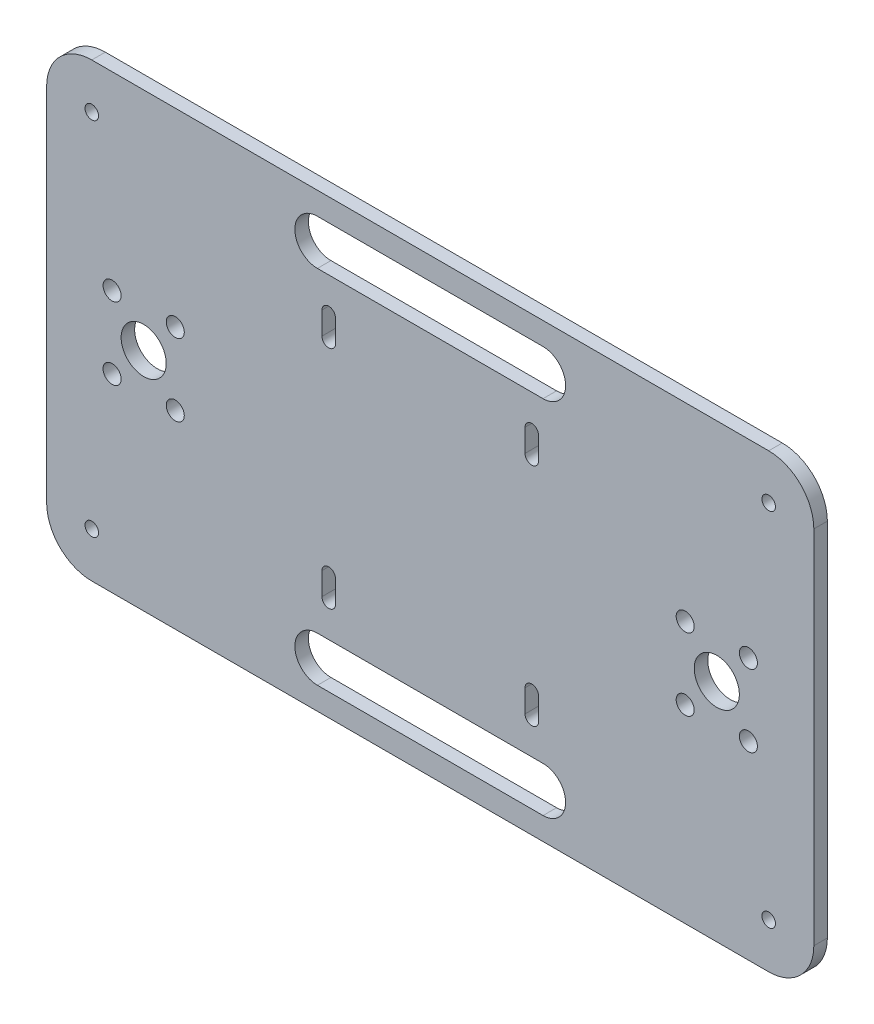
SolidWorks part; units mm, degrees
ref_plane "Front Plane" through (0, 0, 0) normal (0, 0, 1) x (1, 0, 0)
ref_plane "Top Plane" through (0, 0, 0) normal (0, 1, 0) x (1, 0, 0)
ref_plane "Right Plane" through (0, 0, 0) normal (1, 0, 0) x (0, 0, -1)
sketch "Sketch1" plane through (0, 0, 0) normal (0, 0, 1) x (1, 0, 0)
  line L0 (-85, 0) -> (85, 0) construction
  line L1 (-75, 50) -> (75, 50)
  line L2 (-85, 40) -> (-85, -40)
  line L3 (-75, -50) -> (75, -50)
  line L4 (85, 40) -> (85, -40)
  line L5 (-85, 50) -> (85, -50) construction
  line L6 (-85, -50) -> (85, 50) construction
  line L7 (0, 50) -> (0, -50) construction
  line L8 (-63.5, 20) -> (-63.5, -20) construction
  line L9 (-85, 20) -> (-42, 20)
  line L10 (-85, 20) -> (-85, -20)
  line L11 (-85, -20) -> (-42, -20)
  line L12 (-42, 20) -> (-42, -20)
  line L13 (-85, 20) -> (-42, -20) construction
  line L14 (-85, -20) -> (-42, 20) construction
  line L15 (85, -20) -> (42, -20)
  line L16 (42, 20) -> (42, -20)
  line L17 (85, 20) -> (42, 20)
  line L18 (85, 20) -> (85, -20)
  line L19 (-25, 40) -> (25, 40) construction
  line L20 (-25, 45) -> (25, 45)
  line L21 (-25, 35) -> (25, 35)
  line L22 (-25, -40) -> (25, -40) construction
  line L23 (-25, -45) -> (25, -45)
  line L24 (-25, -35) -> (25, -35)
  line L25 (-22.5, -27.5) -> (-22.5, -22.5) construction
  line L26 (-22.5, -25) -> (22.5, -25) construction
  line L27 (-22.5, -25) -> (-22.5, 25) construction
  line L28 (-22.5, 25) -> (22.5, 25) construction
  line L29 (22.5, -25) -> (22.5, 25) construction
  line L30 (-22.5, -25) -> (22.5, 25) construction
  line L31 (-22.5, 25) -> (22.5, -25) construction
  line L34 (-24, -27.5) -> (-24, -22.5)
  line L35 (-21, -27.5) -> (-21, -22.5)
  line L36 (-22.5, 27.5) -> (-22.5, 22.5) construction
  line L37 (-24, 27.5) -> (-24, 22.5)
  line L38 (-21, 27.5) -> (-21, 22.5)
  line L39 (22.5, 27.5) -> (22.5, 22.5) construction
  line L40 (24, 27.5) -> (24, 22.5)
  line L41 (21, 27.5) -> (21, 22.5)
  line L42 (22.5, -27.5) -> (22.5, -22.5) construction
  line L43 (24, -27.5) -> (24, -22.5)
  line L44 (21, -27.5) -> (21, -22.5)
  circle A0 centre (-70.5, 8) radius 2
  circle A1 centre (-70.5, -8) radius 2
  circle A2 centre (-56.5, -8) radius 2
  circle A3 centre (-56.5, 8) radius 2
  circle A4 centre (70.5, -8) radius 2
  circle A5 centre (56.5, -8) radius 2
  circle A6 centre (56.5, 8) radius 2
  circle A7 centre (70.5, 8) radius 2
  arc A8 (-85, -40) -> (-75, -50) centre (-75, -40) ccw
  arc A9 (75, -50) -> (85, -40) centre (75, -40) ccw
  arc A10 (75, 50) -> (85, 40) centre (75, 40) cw
  arc A11 (-85, 40) -> (-75, 50) centre (-75, 40) cw
  arc A12 (-25, 45) -> (-25, 35) centre (-25, 40) ccw
  arc A13 (25, 35) -> (25, 45) centre (25, 40) ccw
  arc A14 (-25, -45) -> (-25, -35) centre (-25, -40) cw
  arc A15 (25, -35) -> (25, -45) centre (25, -40) cw
  circle A16 centre (-75, -40) radius 1.5
  circle A17 centre (-75, 40) radius 1.5
  circle A18 centre (75, 40) radius 1.5
  circle A19 centre (75, -40) radius 1.5
  arc A26 (-24, -27.5) -> (-21, -27.5) centre (-22.5, -27.5) ccw
  arc A27 (-21, -22.5) -> (-24, -22.5) centre (-22.5, -22.5) ccw
  arc A28 (-24, 27.5) -> (-21, 27.5) centre (-22.5, 27.5) cw
  arc A29 (-21, 22.5) -> (-24, 22.5) centre (-22.5, 22.5) cw
  arc A30 (24, 27.5) -> (21, 27.5) centre (22.5, 27.5) ccw
  arc A31 (21, 22.5) -> (24, 22.5) centre (22.5, 22.5) ccw
  arc A32 (24, -27.5) -> (21, -27.5) centre (22.5, -27.5) cw
  arc A33 (21, -22.5) -> (24, -22.5) centre (22.5, -22.5) cw
  circle A34 centre (-63.5, 0) radius 5
  circle A35 centre (63.5, 0) radius 5
  point P0 (0, 0)
  point P10 (-63.5, 0)
  point P51 (0, 40)
  point P58 (0, -40)
  point P72 (0, 0)
  point P78 (-22.5, -25)
  point P86 (-22.5, 25)
  point P92 (22.5, 25)
  point P99 (22.5, -25)
  dimension "D6" = 4
  dimension "D9" = 10
  dimension "D11" = 5
  dimension "D13" = 3
  dimension "D16" = 3
  dimension "D22" = 1.5
  dimension "D23" = 5
  dimension "D24" = 10
  dimension "D1" = 170
  dimension "D2" = 100
  dimension "D3" = 43
  dimension "D4" = 40
  dimension "D5" = 63.5
  dimension "D7" = 7
  dimension "D8" = 8
  dimension "D10" = 50
  dimension "D12" = 40
  dimension "D14" = 75
  dimension "D15" = 40
  dimension "D17" = 40
  dimension "D18" = 75
  dimension "D19" = 75
  dimension "D20" = 50
  dimension "D21" = 45
extrude "Boss-Extrude1" add sketch "Sketch1" along normal blind 3 contours A11 L2 L9 L12 L11 A8 L3 A9 L4 L15 L16 L17 A10 L1 A13 L21 A12 L20 L24 A15 L23 A14 | L12 L9 L2 L11 A1 A0 A2 A3 | L4 L17 L16 L15 A5 A4 A6 A7
